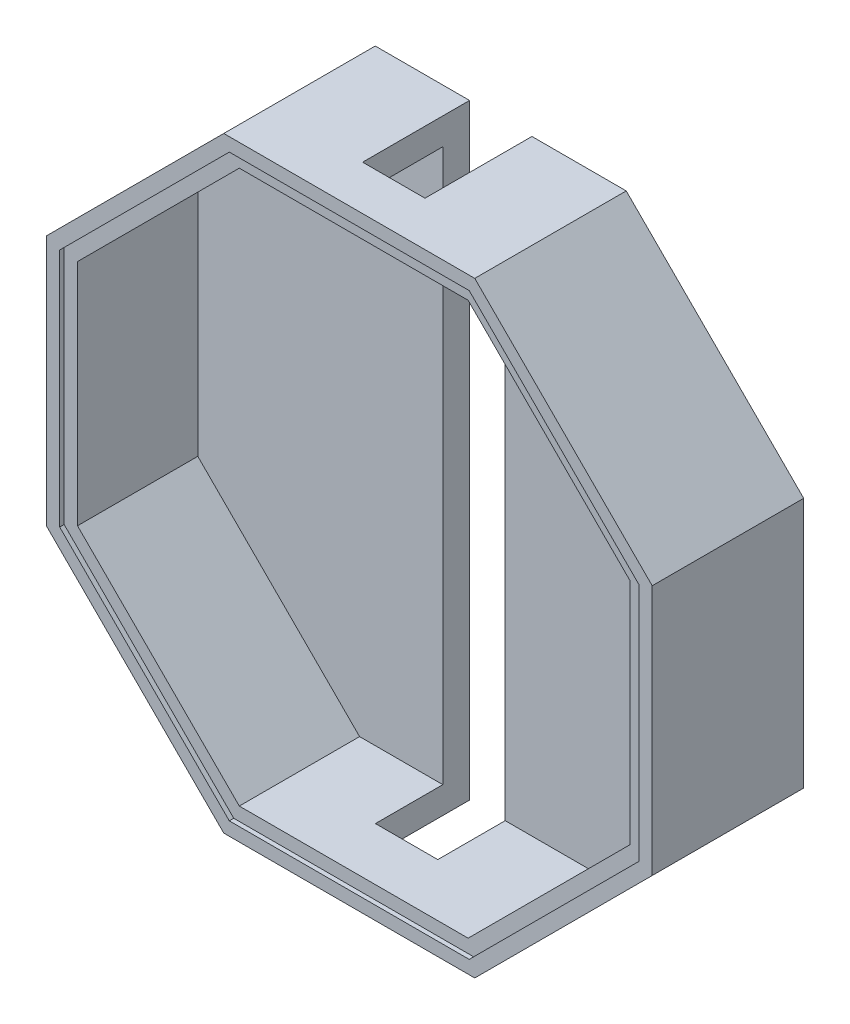
SolidWorks part; units mm, degrees
ref_plane "Front Plane" through (0, 0, 0) normal (0, 0, 1) x (1, 0, 0)
ref_plane "Top Plane" through (0, 0, 0) normal (0, 1, 0) x (1, 0, 0)
ref_plane "Right Plane" through (0, 0, 0) normal (1, 0, 0) x (0, 0, -1)
sketch "Sketch1" plane through (0, 0, 0) normal (0, 0, 1) x (1, 0, 0)
  line L1 (215.9, 215.9) -> (-215.9, 215.9)
  line L2 (215.9, 215.9) -> (215.9, -215.9)
  line L3 (215.9, -215.9) -> (-215.9, -215.9)
  line L4 (-215.9, 215.9) -> (-215.9, -215.9)
  line L5 (215.9, 215.9) -> (-215.9, -215.9) construction
  line L6 (215.9, -215.9) -> (-215.9, 215.9) construction
  point P0 (0, 0)
  dimension "D1" = 431.8
  dimension "D2" = 431.8
extrude "Boss-Extrude1" add sketch "Sketch1" along normal blind 44.45 and the other way blind 63.5
sketch "Sketch2" plane through (0, 0, 44.45) normal (0, 0, 1) x (1, 0, 0)
  line L0 (-215.9, 215.9) -> (-215.9, -215.9) construction
  line L1 (-215.9, 89.4287) -> (-215.9, -89.4287)
  line L2 (-215.9, -89.4287) -> (-89.4287, -215.9)
  line L3 (-89.4287, -215.9) -> (89.4287, -215.9)
  line L4 (89.4287, -215.9) -> (215.9, -89.4287)
  line L5 (215.9, -89.4287) -> (215.9, 89.4287)
  line L6 (215.9, 89.4287) -> (89.4287, 215.9)
  line L7 (89.4287, 215.9) -> (-89.4287, 215.9)
  line L8 (-89.4287, 215.9) -> (-215.9, 89.4287)
  circle A0 centre (0, 0) radius 215.9 construction
  point P1 (-215.9, -81.3136)
  point P14 (-215.9, 88.2748)
  point P15 (-215.9, 90.2359)
extrude "Cut-Extrude1" cut sketch "Sketch2" against normal through all both and the other way through all flip side to cut
sketch "Sketch6" plane through (0, 0, 0) normal (1, 0, 0) x (0, 0, -1)
  line L0 (-12.7, 215.9) -> (-3.175, -215.9)
  line L1 (63.5, 215.9) -> (-44.45, 215.9) construction
  line L2 (63.5, -215.9) -> (-44.45, -215.9) construction
  line L3 (-3.175, -215.9) -> (63.5, -215.9)
  line L4 (63.5, -215.9) -> (63.5, 215.9)
  line L5 (63.5, 215.9) -> (-12.7, 215.9)
  line L6 (-44.45, 89.4287) -> (-44.45, 215.9) construction
  line L7 (-44.45, -215.9) -> (-44.45, -89.4287) construction
  dimension "D1" = 31.75
  dimension "D2" = 41.275
extrude "Cut-Extrude5" cut sketch "Sketch6" against normal mid plane 44.45
shell "Shell1" thickness 19.05
sketch "Sketch4" plane through (0, 0, 44.45) normal (0, 0, 1) x (1, 0, 0)
  line L16 (85.4833, 206.375) -> (-85.4833, 206.375)
  line L17 (-85.4833, 206.375) -> (-206.375, 85.4833)
  line L18 (-206.375, 85.4833) -> (-206.375, -85.4833)
  line L19 (-206.375, -85.4833) -> (-85.4833, -206.375)
  line L20 (-85.4833, -206.375) -> (85.4833, -206.375)
  line L21 (85.4833, -206.375) -> (206.375, -85.4833)
  line L22 (206.375, -85.4833) -> (206.375, 85.4833)
  line L23 (206.375, 85.4833) -> (85.4833, 206.375)
  line L24 (85.4833, 206.375) -> (-85.4833, 206.375)
  line L25 (-85.4833, 206.375) -> (-206.375, 85.4833)
  line L26 (-206.375, 85.4833) -> (-206.375, -85.4833)
  line L27 (-206.375, -85.4833) -> (-85.4833, -206.375)
  line L28 (-85.4833, -206.375) -> (85.4833, -206.375)
  line L29 (85.4833, -206.375) -> (206.375, -85.4833)
  line L30 (206.375, -85.4833) -> (206.375, 85.4833)
  line L31 (206.375, 85.4833) -> (85.4833, 206.375)
  dimension "D1" = 9.525
extrude "Cut-Extrude3" cut sketch "Sketch4" against normal blind 3.175
sketch "Sketch5" plane through (0, -196.85, 0) normal (0, 1, 0) x (1, 0, 0)
  line L0 (81.5379, 44.45) -> (41.275, 44.45) construction
  line L1 (-58.6274, 44.45) -> (61.4065, 44.45)
  line L2 (-58.6274, 44.45) -> (-58.6274, -37.2495)
  line L3 (-58.6274, -37.2495) -> (61.4065, -37.2495)
  line L4 (61.4065, 44.45) -> (61.4065, -37.2495)
  line L5 (-58.6274, 44.45) -> (61.4065, -37.2495) construction
  line L6 (-58.6274, -37.2495) -> (61.4065, 44.45) construction
  point P4 (1.3895, 3.6003)
  point P5 (41.275, -19.05)
  point P7 (-41.275, 44.45)
  point P9 (61.4065, 44.45)
  point P12 (-59.3921, 44.45)
  point P13 (-58.6274, -37.2495)
extrude "Cut-Extrude4" cut sketch "Sketch5" along normal up to surface (393.7 mm away) up to face at (0, 196.85, -4.0726)
